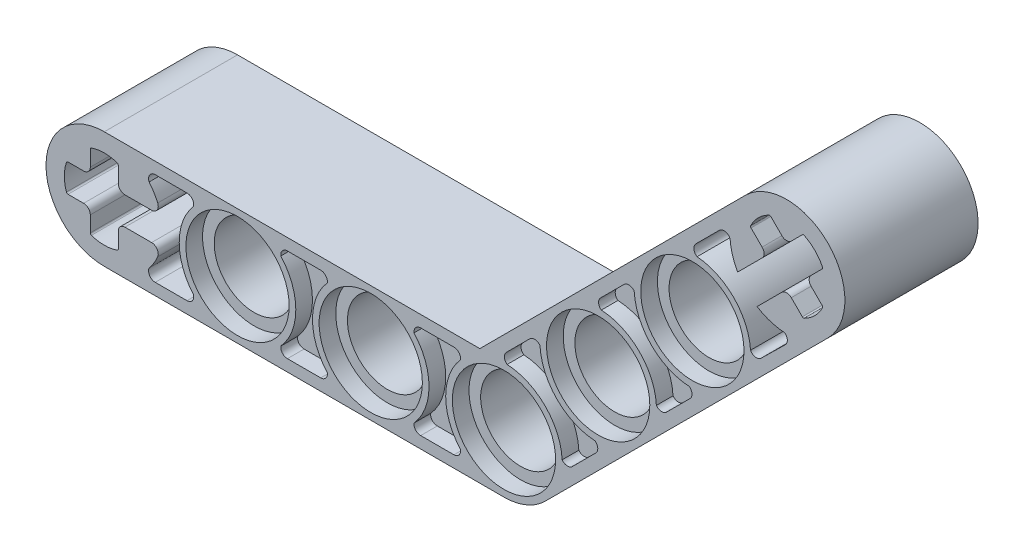
SolidWorks part; units mm, degrees
ref_plane "Front Plane" through (0, 0, 0) normal (0, 0, 1) x (1, 0, 0)
ref_plane "Top Plane" through (0, 0, 0) normal (0, 1, 0) x (1, 0, 0)
ref_plane "Right Plane" through (0, 0, 0) normal (1, 0, 0) x (0, 0, -1)
sketch "Sketch2" plane through (0, 0, 0) normal (0, 0, 1) x (1, 0, 0)
  line L0 (0, 0) -> (-12, 0) construction
  line L1 (0, 0) -> (12, 0) construction
  line L2 (-12, 0) -> (12, 0) construction
  line L3 (-12, 3.5) -> (10.5503, 3.5)
  line L4 (-12, -3.5) -> (12, -3.5)
  line L5 (12, 0) -> (28.9706, 16.9706) construction
  line L6 (12, 0) -> (28.9706, 16.9706) construction
  line L7 (10.5503, 3.5) -> (26.4957, 19.4454)
  line L8 (14.4749, -2.4749) -> (31.4454, 14.4957)
  arc A0 (-12, 3.5) -> (-12, -3.5) centre (-12, 0) ccw
  arc A1 (12, -3.5) -> (14.4749, -2.4749) centre (12, 0) ccw
  arc A2 (12, -3.5) -> (14.4749, -2.4749) centre (12, 0) ccw
  arc A3 (31.4454, 14.4957) -> (26.4957, 19.4454) centre (28.9706, 16.9706) ccw
  point P3 (0, 0)
  point P11 (20.4853, 8.4853)
  dimension "D3" = 3.5
  dimension "D4" = 3.5
  dimension "D7" = 3.5
  dimension "D1" = 12
  dimension "D2" = 12
  dimension "D5" = 24
  dimension "D6" = 135
extrude "Boss-Extrude1" add sketch "Sketch2" against normal blind 8 contours L4 A0 L3 L7 A3 L8 A2
sketch "Sketch3" plane through (0, 0, 0) normal (0, 0, 1) x (1, 0, 0)
  circle A2 centre (-4, 0) radius 3.5
  circle A3 centre (4, 0) radius 3.5
  circle A4 centre (12, 0) radius 3.5
  circle A5 centre (-4, 0) radius 2.4
  circle A6 centre (4, 0) radius 2.4
  circle A7 centre (12, 0) radius 2.4
  dimension "D1" = 7
  dimension "D2" = 7
  dimension "D3" = 7
  dimension "D6" = 4.8
  dimension "D7" = 4.8
  dimension "D8" = 4.8
extrude "Cut-Extrude1" cut sketch "Sketch3" against normal blind 8 contours A5 | A6 | A7
sketch "Sketch4" plane through (0, 0, 0) normal (0, 0, 1) x (1, 0, 0)
  line L0 (-11.16, -0.84) -> (-9.7518, -0.84)
  line L2 (-12.84, 2.2482) -> (-12.84, 0.84)
  line L4 (-11.16, 2.2482) -> (-11.16, 0.84)
  line L5 (-12.84, 2.2482) -> (-11.16, -2.2482) construction
  line L6 (-12.84, -2.2482) -> (-11.16, 2.2482) construction
  line L7 (-14.2482, 0.84) -> (-12.84, 0.84)
  line L9 (-14.2482, -0.84) -> (-12.84, -0.84)
  line L11 (-14.2482, 0.84) -> (-9.7518, -0.84) construction
  line L12 (-14.2482, -0.84) -> (-9.7518, 0.84) construction
  line L13 (-12.84, -0.84) -> (-12.84, -2.2482)
  line L14 (-11.16, 0.84) -> (-9.7518, 0.84)
  line L15 (-11.16, -0.84) -> (-11.16, -2.2482)
  arc A0 (-11.16, 2.2482) -> (-12.84, 2.2482) centre (-12, 0) ccw
  arc A1 (-14.2482, 0.84) -> (-14.2482, -0.84) centre (-12, 0) ccw
  arc A2 (-12.84, -2.2482) -> (-11.16, -2.2482) centre (-12, 0) ccw
  arc A3 (-9.7518, -0.84) -> (-9.7518, 0.84) centre (-12, 0) ccw
  dimension "D1" = 4.8
  dimension "D2" = 1.68
  dimension "D3" = 1.68
extrude "Cut-Extrude2" cut sketch "Sketch4" against normal through all
sketch "Sketch5" plane through (0, 0, 0) normal (0, 0, 1) x (1, 0, 0)
  circle A2 centre (17.6569, 5.6569) radius 2.4
  circle A3 centre (23.3137, 11.3137) radius 2.4
  dimension "D1" = 4.8
  dimension "D2" = 4.8
extrude "Cut-Extrude3" cut sketch "Sketch5" against normal through all
sketch "Sketch6" plane through (0, 0, 0) normal (0, 0, 1) x (1, 0, 0)
  circle A0 centre (-4, 0) radius 3.1
  circle A1 centre (4, 0) radius 3.1
  circle A2 centre (12, 0) radius 3.1
  circle A3 centre (17.6569, 5.6569) radius 3.1
  circle A4 centre (23.3137, 11.3137) radius 3.1
  dimension "D1" = 6.2
  dimension "D2" = 6.2
  dimension "D3" = 6.2
  dimension "D4" = 6.2
  dimension "D5" = 6.2
extrude "Cut-Extrude4" cut sketch "Sketch6" against normal blind 1
sketch "Sketch7" plane through (0, 0, 0) normal (0, 0, 1) x (1, 0, 0)
  line L0 (-9.7518, 0.84) -> (-8.6023, 0.84)
  line L1 (-9.7518, -0.84) -> (-8.6023, -0.84)
  line L2 (-9.7518, 0.84) -> (-9.7518, -0.84)
  line L5 (-8.9424, 2.8) -> (-7.0324, 2.8)
  line L10 (-8.9424, -2.8) -> (-7.0324, -2.8)
  arc A0 (-6.6483, 2.2884) -> (-6.6483, -2.2884) centre (-4, 0) ccw
  arc A1 (-9.307, -2.2355) -> (-8.6023, -0.84) centre (-12, 0) ccw
  arc A4 (-8.9424, 2.8) -> (-9.307, 2.2355) centre (-8.9424, 2.4) ccw
  arc A6 (-9.307, -2.2355) -> (-8.9424, -2.8) centre (-8.9424, -2.4) ccw
  arc A7 (-7.0324, -2.8) -> (-6.6483, -2.2884) centre (-7.0324, -2.4) ccw
  arc A8 (-6.6483, 2.2884) -> (-7.0324, 2.8) centre (-7.0324, 2.4) ccw
  arc A9 (-8.6023, 0.84) -> (-9.307, 2.2355) centre (-12, 0) ccw
  point P13 (-7.9874, 2.4)
  point P21 (-7.9874, -2.4)
  dimension "D1" = 0.4
extrude "Cut-Extrude6" cut sketch "Sketch7" against normal through all
sketch "Sketch9" plane through (0, 0, 0) normal (0, 0, 1) x (1, 0, 0)
  line L3 (-1.0037, 2.8) -> (0.9963, 2.8)
  line L8 (-1.0037, -2.8) -> (0.9963, -2.8)
  arc A0 (-1.3996, -2.3426) -> (-1.3996, 2.3426) centre (-4, 0) ccw
  arc A1 (1.3905, 2.3325) -> (1.3905, -2.3325) centre (4, 0) ccw
  arc A2 (-1.0037, 2.8) -> (-1.3996, 2.3426) centre (-1.0037, 2.4) ccw
  arc A3 (1.3905, 2.3325) -> (0.9963, 2.8) centre (0.9963, 2.4) ccw
  arc A4 (-1.3996, -2.3426) -> (-1.0037, -2.8) centre (-1.0037, -2.4) ccw
  arc A5 (0.9963, -2.8) -> (1.3905, -2.3325) centre (0.9963, -2.4) ccw
  point P15 (-0.0037, 2.4)
  point P23 (-0.0037, -2.4)
  dimension "D2" = 0.4
  dimension "D5" = 0.4
  dimension "D3" = 2
extrude "Cut-Extrude7" cut sketch "Sketch9" against normal blind 1
pattern_linear "LPattern1" count 2 spacing 8 along (1, 0, 0) of "Cut-Extrude7"
sketch "Sketch10" plane through (0, 0, 0) normal (0, 0, 1) x (1, 0, 0)
  line L6 (12.1414, 4.1012) -> (13.5556, 5.5154)
  line L12 (16.1012, 0.1414) -> (17.5154, 1.5556)
  arc A0 (15.4949, 0.189) -> (12.189, 3.4949) centre (12, 0) ccw
  arc A1 (14.162, 5.4679) -> (17.4679, 2.162) centre (17.6569, 5.6569) ccw
  arc A2 (12.1414, 4.1012) -> (12.189, 3.4949) centre (12.4243, 3.8184) ccw
  arc A3 (14.162, 5.4679) -> (13.5556, 5.5154) centre (13.8385, 5.2326) ccw
  arc A4 (15.4949, 0.189) -> (16.1012, 0.1414) centre (15.8184, 0.4243) ccw
  arc A5 (17.5154, 1.5556) -> (17.4679, 2.162) centre (17.2326, 1.8385) ccw
  point P8 (13.1314, 4.5255)
  point P16 (16.5255, 1.1314)
  dimension "D5" = 0.4
  dimension "D8" = 0.4
extrude "Cut-Extrude8" cut sketch "Sketch10" against normal blind 1
sketch "Sketch11" plane through (0, 0, 0) normal (0, 0, 1) x (1, 0, 0)
  line L6 (17.7983, 9.7581) -> (19.2125, 11.1723)
  line L12 (21.7581, 5.7983) -> (23.1723, 7.2125)
  arc A0 (21.1517, 5.8458) -> (17.8458, 9.1517) centre (17.6569, 5.6569) ccw
  arc A1 (19.8188, 11.1247) -> (23.1247, 7.8188) centre (23.3137, 11.3137) ccw
  arc A2 (17.7983, 9.7581) -> (17.8458, 9.1517) centre (18.0811, 9.4752) ccw
  arc A3 (19.8188, 11.1247) -> (19.2125, 11.1723) centre (19.4953, 10.8894) ccw
  arc A4 (21.1517, 5.8458) -> (21.7581, 5.7983) centre (21.4752, 6.0811) ccw
  arc A5 (23.1723, 7.2125) -> (23.1247, 7.8188) centre (22.8894, 7.4953) ccw
  point P8 (18.7882, 10.1823)
  point P16 (22.1823, 6.7882)
  dimension "D5" = 0.4
  dimension "D6" = 0.4
extrude "Cut-Extrude9" cut sketch "Sketch11" against normal blind 1
ref_plane "mirror plane" through (0, 0, -4) normal (0, 0, 1) x (1, 0, 0)
sketch "Sketch14" plane through (20.4853, -15.5147, 0) normal (0, 0, 1) x (0.7071, 0.7071, 0)
  line L0 (28.1306, 16.1306) -> (28.1306, 14.7224)
  line L2 (28.1306, 19.2188) -> (28.1306, 17.8106)
  line L4 (29.8106, 19.2188) -> (29.8106, 17.8106)
  line L5 (28.1306, 19.2188) -> (29.8106, 14.7224) construction
  line L6 (28.1306, 14.7224) -> (29.8106, 19.2188) construction
  line L7 (26.7224, 17.8106) -> (28.1306, 17.8106)
  line L9 (26.7224, 16.1306) -> (28.1306, 16.1306)
  line L11 (26.7224, 17.8106) -> (31.2188, 16.1306) construction
  line L12 (26.7224, 16.1306) -> (31.2188, 17.8106) construction
  line L13 (29.8106, 17.8106) -> (31.2188, 17.8106)
  line L14 (29.8106, 16.1306) -> (31.2188, 16.1306)
  line L15 (29.8106, 16.1306) -> (29.8106, 14.7224)
  line L16 (26.7224, 17.8106) -> (24.8317, 17.8106)
  line L17 (26.7224, 16.1306) -> (24.8317, 16.1306)
  line L18 (24.8317, 16.1306) -> (24.8317, 17.8106)
  arc A2 (29.8106, 19.2188) -> (28.1306, 19.2188) centre (28.9706, 16.9706) ccw
  arc A3 (31.2188, 16.1306) -> (31.2188, 17.8106) centre (28.9706, 16.9706) ccw
  arc A4 (28.1306, 14.7224) -> (29.8106, 14.7224) centre (28.9706, 16.9706) ccw
  dimension "D3" = 1.68
  dimension "D4" = 1.68
extrude "Cut-Extrude11" cut sketch "Sketch14" against normal through all
sketch "Sketch15" plane through (0, 0, 0) normal (0, 0, 1) x (1, 0, 0)
  line L6 (23.5175, 15.4291) -> (24.9317, 16.8434)
  line L11 (27.4403, 11.4445) -> (28.8952, 12.8751)
  arc A0 (26.8062, 11.5428) -> (23.5962, 14.8023) centre (23.3137, 11.3137) ccw
  arc A1 (25.5745, 16.7349) -> (28.8595, 13.4767) centre (29.0666, 16.9706) ccw
  arc A2 (23.5175, 15.4291) -> (23.5962, 14.8023) centre (23.8003, 15.1463) ccw
  arc A3 (25.5745, 16.7349) -> (24.9317, 16.8434) centre (25.2145, 16.5605) ccw
  arc A4 (26.8062, 11.5428) -> (27.4403, 11.4445) centre (27.1598, 11.7297) ccw
  arc A5 (28.8952, 12.8751) -> (28.8595, 13.4767) centre (28.6147, 13.1603) ccw
  point P7 (24.5074, 15.8534)
  point P15 (27.8873, 12.445)
  dimension "D4" = 0.4
  dimension "D6" = 0.4
extrude "Cut-Extrude12" cut sketch "Sketch15" against normal through all
mirror "Mirror1" about plane through (0, 0, -4) normal (0, 0, 1) of "Cut-Extrude9", "Cut-Extrude8", "LPattern1", "Cut-Extrude7", "Cut-Extrude4"
fillet "Fillet1" radius 0.4 1 edges at (-12.84, -0.84, -4)
fillet "Fillet2" radius 0.4 1 edges at (-12.84, 0.84, -4)
fillet "Fillet3" radius 0.4 1 edges at (-11.16, 0.84, -4)
fillet "Fillet4" radius 0.4 1 edges at (-11.16, -0.84, -4)
fillet "Fillet5" radius 0.4 1 edges at (-8.6023, 0.84, -4)
fillet "Fillet6" radius 0.4 1 edges at (-8.6023, -0.84, -4)
fillet "Fillet7" radius 0.4 1 edges at (28.9706, 18.1585, -4)
fillet "Fillet8" radius 0.4 1 edges at (27.7826, 16.9706, -4)
fillet "Fillet9" radius 0.4 1 edges at (30.1585, 16.9706, -4)
fillet "Fillet10" radius 0.4 1 edges at (28.9706, 15.7826, -4)
fillet "Fillet11" radius 0.1 1 edges at (26.7869, 17.9663, -4)
fillet "Fillet12" radius 0.1 1 edges at (27.9748, 19.1542, -4)
fillet "Fillet13" radius 0.1 1 edges at (29.9663, 19.1542, -4)
fillet "Fillet14" radius 0.1 1 edges at (31.1542, 17.9663, -4)
fillet "Fillet15" radius 0.1 1 edges at (31.1542, 15.9748, -4)
fillet "Fillet16" radius 0.1 1 edges at (29.9663, 14.7869, -4)
fillet "Fillet17" radius 0.1 1 edges at (-12.84, 2.2482, -4)
fillet "Fillet18" radius 0.1 1 edges at (-11.16, 2.2482, -4)
fillet "Fillet19" radius 0.1 1 edges at (-12.84, -2.2482, -4)
fillet "Fillet20" radius 0.1 1 edges at (-11.16, -2.2482, -4)
fillet "Fillet21" radius 0.1 1 edges at (-14.2482, 0.84, -4)
fillet "Fillet22" radius 0.1 1 edges at (-14.2482, -0.84, -4)
